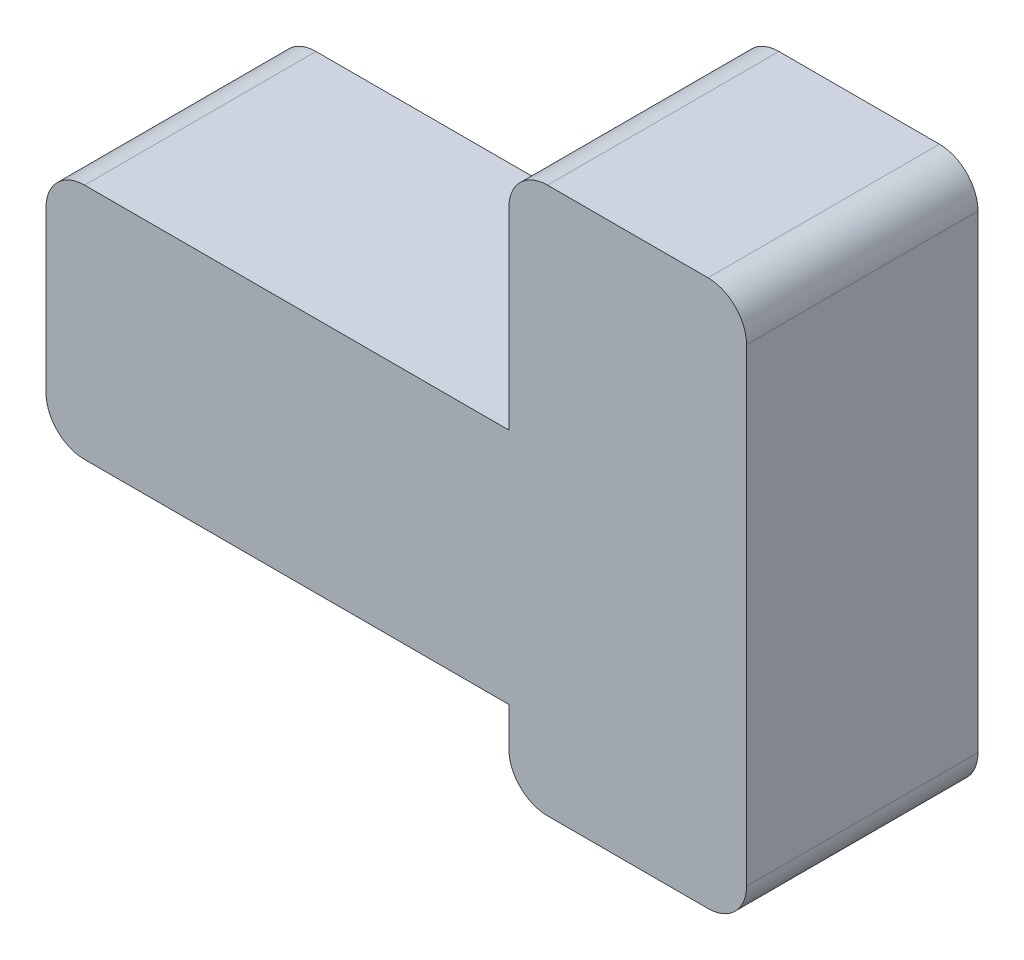
SolidWorks part; units mm, degrees
ref_plane "Front Plane" through (0, 0, 0) normal (0, 0, 1) x (1, 0, 0)
ref_plane "Top Plane" through (0, 0, 0) normal (0, 1, 0) x (1, 0, 0)
ref_plane "Right Plane" through (0, 0, 0) normal (1, 0, 0) x (0, 0, -1)
sketch "Sketch1" plane through (0, 0, 0) normal (0, 0, 1) x (1, 0, 0)
  line L0 (-16.0554, 1.2294) -> (-10.0554, 1.2294)
  line L1 (-10.0554, 1.2294) -> (-10.0554, 0.2294)
  line L2 (-10.0554, 0.2294) -> (-6.9754, 0.2294)
  line L3 (-6.9754, 0.2294) -> (-6.9754, 7.3094)
  line L4 (-6.9754, 7.3094) -> (-10.0554, 7.3094)
  line L5 (-10.0554, 7.3094) -> (-10.0554, 4.3094)
  line L6 (-10.0554, 4.3094) -> (-16.0554, 4.3094)
  line L7 (-16.0554, 4.3094) -> (-16.0554, 1.2294)
  dimension "D1" = 3.08
  dimension "D2" = 6
  dimension "D3" = 1
  dimension "D4" = 3
  dimension "D5" = 3.08
  dimension "D6" = 7.08
extrude "Boss-Extrude1" add sketch "Sketch1" along normal blind 3
fillet "Fillet1" radius 0.5 6 edges at (-16.0554, 1.2294, 1.5) (-16.0554, 4.3094, 1.5) (-6.9754, 7.3094, 1.5) (-10.0554, 7.3094, 1.5) (-6.9754, 0.2294, 1.5) (-10.0554, 0.2294, 1.5)
